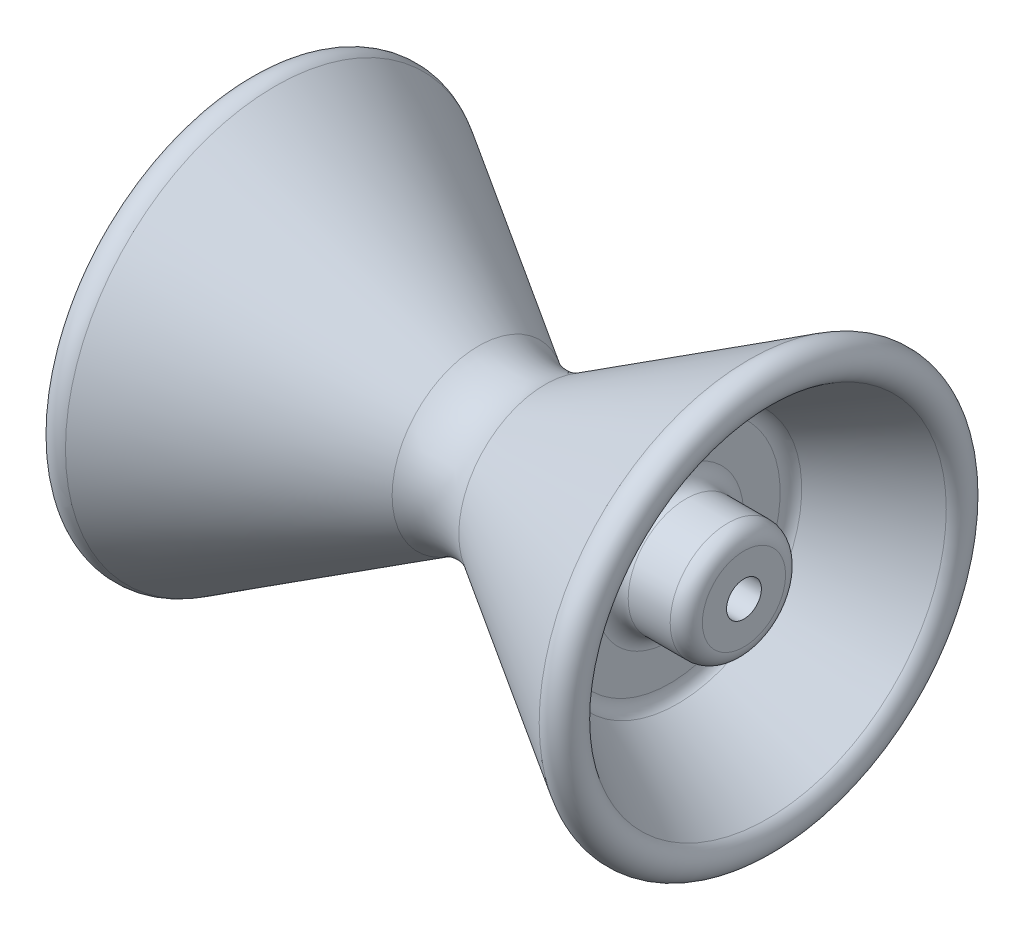
SolidWorks part; units mm, degrees
ref_plane "Front Plane" through (0, 0, 0) normal (0, 0, 1) x (1, 0, 0)
ref_plane "Top Plane" through (0, 0, 0) normal (0, 1, 0) x (1, 0, 0)
ref_plane "Right Plane" through (0, 0, 0) normal (1, 0, 0) x (0, 0, -1)
sketch "Sketch1" plane through (0, 0, 0) normal (0, 0, 1) x (1, 0, 0)
  line L0 (-361.4801, -40.4437) -> (270.7763, -40.4437) construction
  line L1 (0, 162.1243) -> (0, -182.6031) construction
  line L2 (-268.1401, 21.1961) -> (-215.9852, 21.1961)
  line L3 (-185.9852, 51.1961) -> (-185.9852, 96.6837)
  line L4 (-200.4552, 122.3512) -> (-312.3241, 190.037)
  line L5 (-299.3824, 211.4266) -> (-46.59, 58.4755)
  line L6 (-127.0736, 101.9459) -> (-128.0693, 102.9416)
  line L7 (-155.9852, 42.2295) -> (-155.9852, -8.8039)
  line L8 (-110.4552, 67.897) -> (-53.2577, 33.2899)
  line L9 (-155.9852, -8.8039) -> (-278.1401, -8.8039)
  line L10 (-278.1401, -8.8039) -> (-278.1401, 11.1961)
  line L11 (278.1401, -8.8039) -> (278.1401, 11.1961)
  line L12 (155.9852, -8.8039) -> (278.1401, -8.8039)
  line L13 (110.4552, 67.897) -> (53.2577, 33.2899)
  line L14 (155.9852, 42.2295) -> (155.9852, -8.8039)
  line L15 (127.0736, 101.9459) -> (128.0693, 102.9416)
  line L16 (299.3824, 211.4266) -> (46.59, 58.4755)
  line L17 (200.4552, 122.3512) -> (312.3241, 190.037)
  line L18 (185.9852, 51.1961) -> (185.9852, 96.6837)
  line L19 (268.1401, 21.1961) -> (215.9852, 21.1961)
  arc A0 (-312.3241, 190.037) -> (-299.3824, 211.4266) centre (-305.8532, 200.7318) cw
  arc A1 (-215.9852, 21.1961) -> (-185.9852, 51.1961) centre (-215.9852, 51.1961) ccw
  arc A2 (-185.9852, 96.6837) -> (-200.4552, 122.3512) centre (-215.9852, 96.6837) ccw
  arc A3 (-268.1401, 21.1961) -> (-278.1401, 11.1961) centre (-268.1401, 11.1961) ccw
  arc A4 (-110.4552, 67.897) -> (-155.9852, 42.2295) centre (-125.9852, 42.2295) ccw
  arc A5 (-46.59, 58.4755) -> (46.59, 58.4755) centre (0, 135.4779) ccw
  arc A6 (-53.2577, 33.2899) -> (0, 16.7128) centre (6.8973, 132.712) ccw
  arc A7 (53.2577, 33.2899) -> (0, 16.7128) centre (-6.8973, 132.712) cw
  arc A8 (110.4552, 67.897) -> (155.9852, 42.2295) centre (125.9852, 42.2295) cw
  arc A9 (268.1401, 21.1961) -> (278.1401, 11.1961) centre (268.1401, 11.1961) cw
  arc A10 (185.9852, 96.6837) -> (200.4552, 122.3512) centre (215.9852, 96.6837) cw
  arc A11 (215.9852, 21.1961) -> (185.9852, 51.1961) centre (215.9852, 51.1961) cw
  arc A12 (312.3241, 190.037) -> (299.3824, 211.4266) centre (305.8532, 200.7318) ccw
  point P26 (-316.548, 207.2026)
  point P31 (-81.8565, 50.5935)
  dimension "D1" = 12.5
  dimension "D2" = 30
  dimension "D3" = 10
  dimension "D4" = 30
  dimension "D7" = 90
  dimension "D8" = 116.2041
  dimension "D5" = 30
  dimension "D6" = 316.548
  dimension "D9" = 25
  dimension "D10" = 25
  dimension "D11" = 30
revolve "Revolve-Thin4" add sketch "Sketch1" angle 360 about L0
